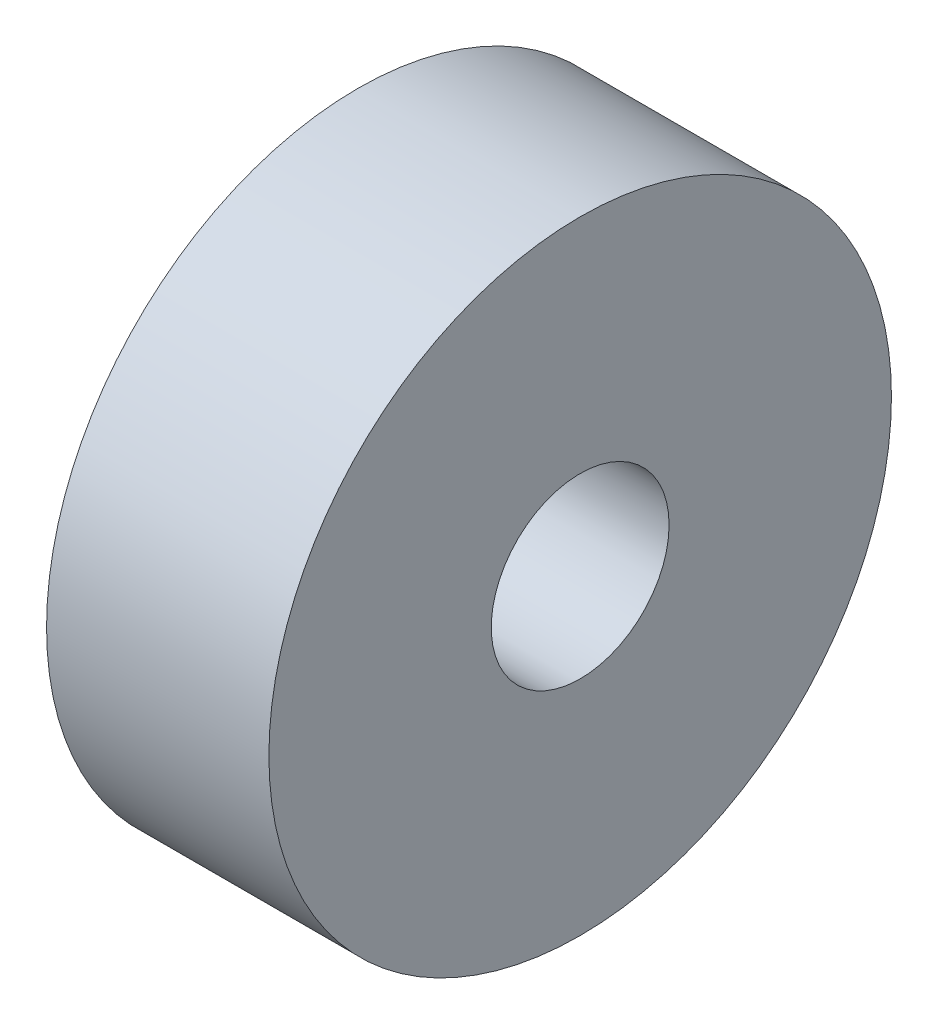
SolidWorks part; units mm, degrees
ref_plane "Front Plane" through (0, 0, 0) normal (0, 0, 1) x (1, 0, 0)
ref_plane "Top Plane" through (0, 0, 0) normal (0, 1, 0) x (1, 0, 0)
ref_plane "Right Plane" through (0, 0, 0) normal (1, 0, 0) x (0, 0, -1)
sketch "Sketch1" plane through (0, 0, 0) normal (1, 0, 0) x (0, 0, -1)
  circle A0 centre (0, 0) radius 4
  circle A1 centre (0, 0) radius 14
  dimension "D1" = 8
  dimension "D2" = 10
extrude "Boss-Extrude1" add sketch "Sketch1" along normal blind 10
